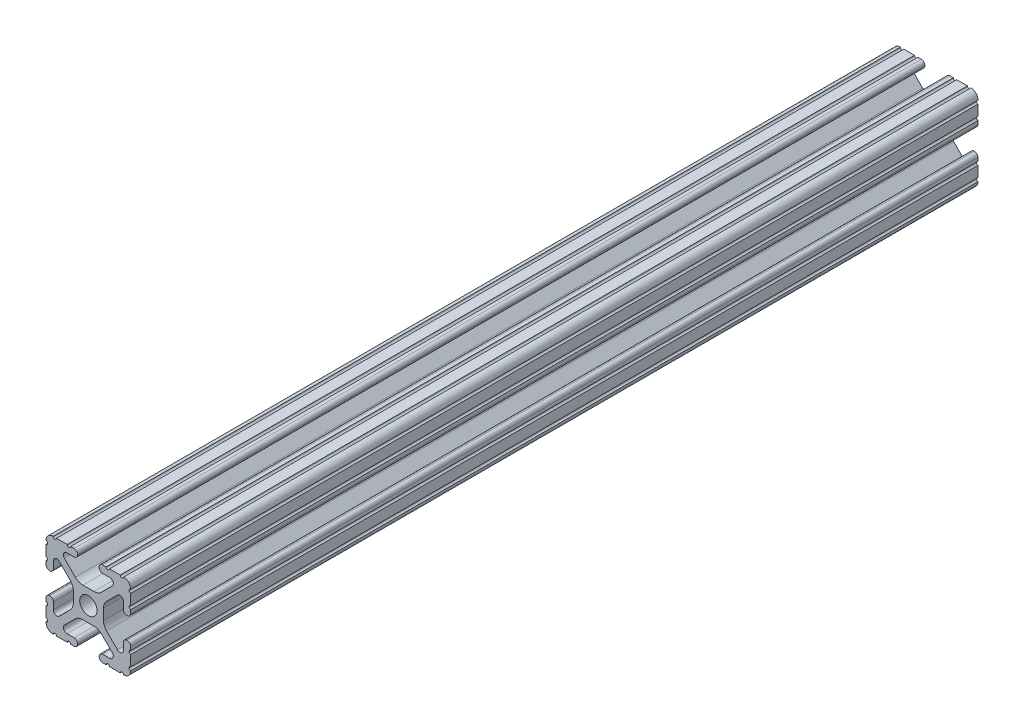
SolidWorks part; units mm, degrees
material "6061 Alloy"
ref_plane "Front Plane" through (0, 0, 0) normal (0, 0, 1) x (1, 0, 0)
ref_plane "Top Plane" through (0, 0, 0) normal (0, 1, 0) x (1, 0, 0)
ref_plane "Right Plane" through (0, 0, 0) normal (1, 0, 0) x (0, 0, -1)
sketch "Sketch1" plane through (0, 0, 0) normal (0, 0, 1) x (1, 0, 0)
  line L88 (-7.1797, -8.6452) -> (-3.9523, -5.4237)
  line L89 (-1.7093, -4.4958) -> (1.7093, -4.4958)
  line L90 (3.9523, -5.4237) -> (7.1797, -8.6452)
  line L91 (6.4164, -10.4902) -> (4.2875, -10.4902)
  line L92 (3.2385, -11.5392) -> (3.2385, -11.651)
  line L93 (4.2875, -12.7) -> (5.3171, -12.7)
  line L94 (6.3331, -12.7) -> (9.5504, -12.7)
  line L95 (12.7, -9.5504) -> (12.7, -6.3331)
  line L96 (12.7, -5.3171) -> (12.7, -4.2875)
  line L97 (11.651, -3.2385) -> (11.5392, -3.2385)
  line L98 (10.4902, -4.2875) -> (10.4902, -6.4021)
  line L99 (8.7371, -7.1294) -> (5.441, -3.8408)
  line L100 (4.5085, -1.5932) -> (4.5085, 1.5932)
  line L101 (5.441, 3.8408) -> (8.7371, 7.1294)
  line L102 (10.4902, 6.4021) -> (10.4902, 4.2875)
  line L103 (11.5392, 3.2385) -> (11.651, 3.2385)
  line L104 (12.7, 4.2875) -> (12.7, 5.3171)
  line L105 (12.7, 6.3331) -> (12.7, 9.5504)
  line L106 (9.5504, 12.7) -> (6.3331, 12.7)
  line L107 (5.3171, 12.7) -> (4.2875, 12.7)
  line L108 (3.2385, 11.651) -> (3.2385, 11.5392)
  line L109 (4.2875, 10.4902) -> (6.4768, 10.4902)
  line L110 (7.207, 8.7244) -> (3.8983, 5.4232)
  line L111 (1.6558, 4.4958) -> (-1.6558, 4.4958)
  line L112 (-3.8983, 5.4232) -> (-7.207, 8.7244)
  line L113 (-6.4768, 10.4902) -> (-4.2875, 10.4902)
  line L114 (-3.2385, 11.5392) -> (-3.2385, 11.651)
  line L115 (-4.2875, 12.7) -> (-5.3171, 12.7)
  line L116 (-6.3331, 12.7) -> (-9.5504, 12.7)
  line L117 (-12.7, 9.5504) -> (-12.7, 6.3331)
  line L118 (-12.7, 5.3171) -> (-12.7, 4.2875)
  line L119 (-11.651, 3.2385) -> (-11.5392, 3.2385)
  line L120 (-10.4902, 4.2875) -> (-10.4902, 6.4021)
  line L121 (-8.7371, 7.1294) -> (-5.441, 3.8408)
  line L122 (-4.5085, 1.5932) -> (-4.5085, -1.5932)
  line L123 (-5.441, -3.8408) -> (-8.7371, -7.1294)
  line L124 (-10.4902, -6.4021) -> (-10.4902, -4.2875)
  line L125 (-11.5392, -3.2385) -> (-11.651, -3.2385)
  line L126 (-12.7, -4.2875) -> (-12.7, -5.3171)
  line L127 (-12.7, -6.3331) -> (-12.7, -9.5504)
  line L128 (-9.5504, -12.7) -> (-6.3331, -12.7)
  line L129 (-5.3171, -12.7) -> (-4.2875, -12.7)
  line L130 (-3.2385, -11.651) -> (-3.2385, -11.5392)
  line L131 (-4.2875, -10.4902) -> (-6.4164, -10.4902)
  circle A1 centre (0, 0) radius 2.6035
  arc A104 (-7.1797, -8.6452) -> (-6.4164, -10.4902) centre (-6.4164, -9.4098) ccw
  arc A105 (-1.7093, -4.4958) -> (-3.9523, -5.4237) centre (-1.7093, -7.6708) ccw
  arc A106 (3.9523, -5.4237) -> (1.7093, -4.4958) centre (1.7093, -7.6708) ccw
  arc A107 (6.4164, -10.4902) -> (7.1797, -8.6452) centre (6.4164, -9.4098) ccw
  arc A108 (4.2875, -10.4902) -> (3.2385, -11.5392) centre (4.2875, -11.5392) ccw
  arc A109 (3.2385, -11.651) -> (4.2875, -12.7) centre (4.2875, -11.651) ccw
  arc A110 (6.3331, -12.7) -> (5.3171, -12.7) centre (5.8251, -12.7) ccw
  arc A111 (10.5664, -12.6998) -> (9.5504, -12.7) centre (10.0584, -12.7) ccw
  arc A112 (10.5664, -12.6998) -> (12.6998, -10.5664) centre (10.5918, -10.5918) ccw
  arc A113 (12.7, -9.5504) -> (12.6998, -10.5664) centre (12.7, -10.0584) ccw
  arc A114 (12.7, -5.3171) -> (12.7, -6.3331) centre (12.7, -5.8251) ccw
  arc A115 (12.7, -4.2875) -> (11.651, -3.2385) centre (11.651, -4.2875) ccw
  arc A116 (11.5392, -3.2385) -> (10.4902, -4.2875) centre (11.5392, -4.2875) ccw
  arc A117 (8.7371, -7.1294) -> (10.4902, -6.4021) centre (9.4628, -6.4021) ccw
  arc A118 (4.5085, -1.5932) -> (5.441, -3.8408) centre (7.6835, -1.5932) ccw
  arc A119 (5.441, 3.8408) -> (4.5085, 1.5932) centre (7.6835, 1.5932) ccw
  arc A120 (10.4902, 6.4021) -> (8.7371, 7.1294) centre (9.4628, 6.4021) ccw
  arc A121 (10.4902, 4.2875) -> (11.5392, 3.2385) centre (11.5392, 4.2875) ccw
  arc A122 (11.651, 3.2385) -> (12.7, 4.2875) centre (11.651, 4.2875) ccw
  arc A123 (12.7, 6.3331) -> (12.7, 5.3171) centre (12.7, 5.8251) ccw
  arc A124 (12.6998, 10.5664) -> (12.7, 9.5504) centre (12.7, 10.0584) ccw
  arc A125 (12.6998, 10.5664) -> (10.5664, 12.6998) centre (10.5918, 10.5918) ccw
  arc A126 (9.5504, 12.7) -> (10.5664, 12.6998) centre (10.0584, 12.7) ccw
  arc A127 (5.3171, 12.7) -> (6.3331, 12.7) centre (5.8251, 12.7) ccw
  arc A128 (4.2875, 12.7) -> (3.2385, 11.651) centre (4.2875, 11.651) ccw
  arc A129 (3.2385, 11.5392) -> (4.2875, 10.4902) centre (4.2875, 11.5392) ccw
  arc A130 (7.207, 8.7244) -> (6.4768, 10.4902) centre (6.4768, 9.4563) ccw
  arc A131 (1.6558, 4.4958) -> (3.8983, 5.4232) centre (1.6558, 7.6708) ccw
  arc A132 (-3.8983, 5.4232) -> (-1.6558, 4.4958) centre (-1.6558, 7.6708) ccw
  arc A133 (-6.4768, 10.4902) -> (-7.207, 8.7244) centre (-6.4768, 9.4563) ccw
  arc A134 (-4.2875, 10.4902) -> (-3.2385, 11.5392) centre (-4.2875, 11.5392) ccw
  arc A135 (-3.2385, 11.651) -> (-4.2875, 12.7) centre (-4.2875, 11.651) ccw
  arc A136 (-6.3331, 12.7) -> (-5.3171, 12.7) centre (-5.8251, 12.7) ccw
  arc A137 (-10.5664, 12.6998) -> (-9.5504, 12.7) centre (-10.0584, 12.7) ccw
  arc A138 (-10.5664, 12.6998) -> (-12.6998, 10.5664) centre (-10.5918, 10.5918) ccw
  arc A139 (-12.7, 9.5504) -> (-12.6998, 10.5664) centre (-12.7, 10.0584) ccw
  arc A140 (-12.7, 5.3171) -> (-12.7, 6.3331) centre (-12.7, 5.8251) ccw
  arc A141 (-12.7, 4.2875) -> (-11.651, 3.2385) centre (-11.651, 4.2875) ccw
  arc A142 (-11.5392, 3.2385) -> (-10.4902, 4.2875) centre (-11.5392, 4.2875) ccw
  arc A143 (-8.7371, 7.1294) -> (-10.4902, 6.4021) centre (-9.4628, 6.4021) ccw
  arc A144 (-4.5085, 1.5932) -> (-5.441, 3.8408) centre (-7.6835, 1.5932) ccw
  arc A145 (-5.441, -3.8408) -> (-4.5085, -1.5932) centre (-7.6835, -1.5932) ccw
  arc A146 (-10.4902, -6.4021) -> (-8.7371, -7.1294) centre (-9.4628, -6.4021) ccw
  arc A147 (-10.4902, -4.2875) -> (-11.5392, -3.2385) centre (-11.5392, -4.2875) ccw
  arc A148 (-11.651, -3.2385) -> (-12.7, -4.2875) centre (-11.651, -4.2875) ccw
  arc A149 (-12.7, -6.3331) -> (-12.7, -5.3171) centre (-12.7, -5.8251) ccw
  arc A150 (-12.6998, -10.5664) -> (-12.7, -9.5504) centre (-12.7, -10.0584) ccw
  arc A151 (-12.6998, -10.5664) -> (-10.5664, -12.6998) centre (-10.5918, -10.5918) ccw
  arc A152 (-9.5504, -12.7) -> (-10.5664, -12.6998) centre (-10.0584, -12.7) ccw
  arc A153 (-5.3171, -12.7) -> (-6.3331, -12.7) centre (-5.8251, -12.7) ccw
  arc A154 (-4.2875, -12.7) -> (-3.2385, -11.651) centre (-4.2875, -11.651) ccw
  arc A155 (-3.2385, -11.5392) -> (-4.2875, -10.4902) centre (-4.2875, -11.5392) ccw
extrude "Boss-Extrude1" add sketch "Sketch1" along normal mid plane 254
equation "\"deep\"= 6in"
equation "\"high\"= 20.5in"
equation "\"wide\"= 14in"
equation "\"Length@Boss-Extrude1\"      = \"wide\""
equation "\"front wide\"= 16in"
